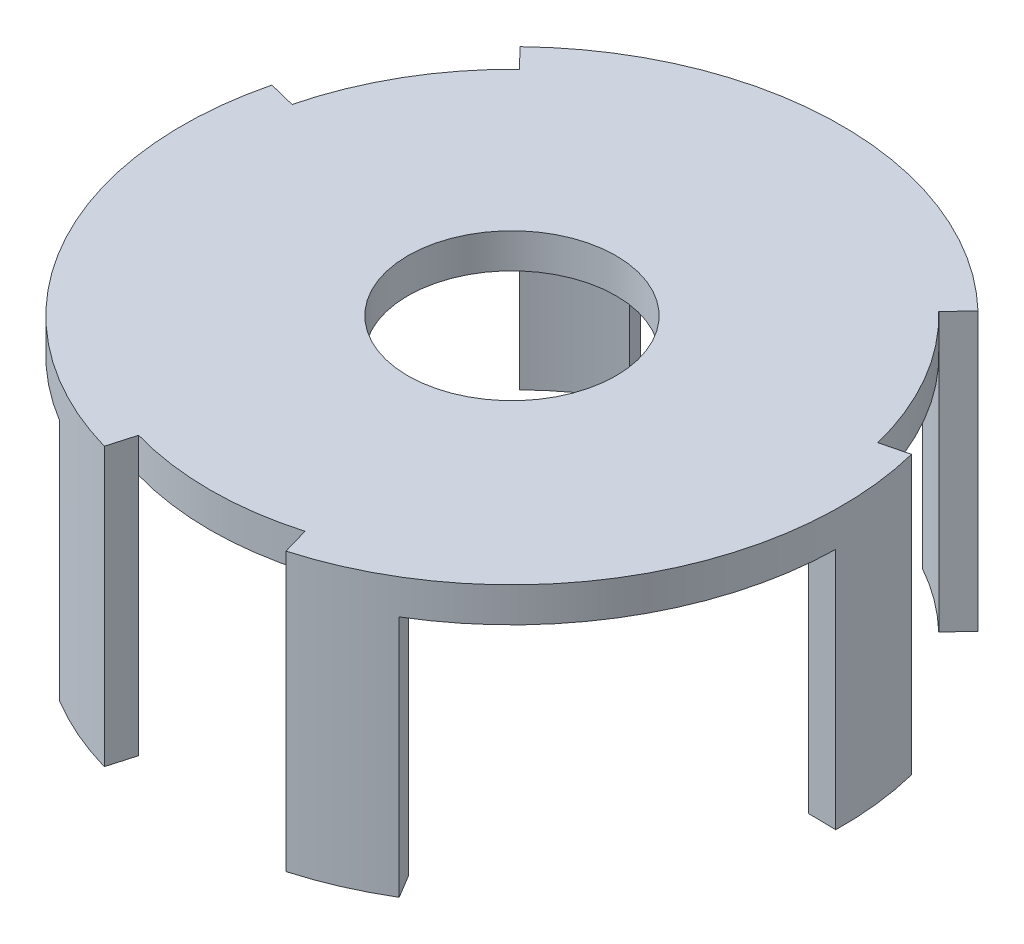
SolidWorks part; units mm, degrees
ref_plane "Alzado" through (0, 0, 0) normal (0, 0, 1) x (1, 0, 0)
ref_plane "Planta" through (0, 0, 0) normal (0, 1, 0) x (1, 0, 0)
ref_plane "Vista lateral" through (0, 0, 0) normal (1, 0, 0) x (0, 0, -1)
sketch "Croquis1" plane through (0, 0, 0) normal (0, 1, 0) x (1, 0, 0)
  circle A0 centre (0, 0) radius 47.5 construction
  dimension "D1" = 95
ref_plane "Plano1" through (0, 40, 0) normal (0, 1, 0) x (1, 0, 0)
sketch "Croquis2" plane through (0, 40, 0) normal (0, 1, 0) x (1, 0, 0)
  circle A0 centre (0, 0) radius 47.5
  circle A1 centre (0, 0) radius 15
  dimension "D1" = 95
  dimension "D2" = 30
extrude "Saliente-Extruir1" add sketch "Croquis2" against normal blind 5
sketch "Croquis3" plane through (0, 35, 0) normal (0, -1, 0) x (1, 0, 0)
  line L0 (-11.9902, 41.8149) -> (-13.0928, 45.6599)
  line L1 (11.9902, 41.8149) -> (13.0928, 45.6599)
  line L2 (0, 0) -> (0, 47.5) construction
  line L3 (-11.9902, 41.8149) -> (0, 0) construction
  line L4 (0, 0) -> (11.9902, 41.8149) construction
  line L5 (30.2176, -31.2913) -> (32.9963, -34.1686)
  line L6 (42.2079, -10.5236) -> (46.089, -11.4913)
  line L7 (-42.2079, -10.5236) -> (-46.089, -11.4913)
  line L8 (-30.2176, -31.2913) -> (-32.9963, -34.1686)
  arc A0 (11.9902, 41.8149) -> (-11.9902, 41.8149) centre (0, 0) ccw
  arc A1 (13.0928, 45.6599) -> (-13.0928, 45.6599) centre (0, 0) ccw
  arc A2 (32.9963, -34.1686) -> (46.089, -11.4913) centre (0, 0) ccw
  arc A3 (30.2176, -31.2913) -> (42.2079, -10.5236) centre (0, 0) ccw
  arc A4 (-46.089, -11.4913) -> (-32.9963, -34.1686) centre (0, 0) ccw
  arc A5 (-42.2079, -10.5236) -> (-30.2176, -31.2913) centre (0, 0) ccw
  point P17 (0, 0)
  dimension "D1" = 87
  dimension "D2" = 95
  dimension "D3" = 32
  dimension "D4" = 16
  dimension "D5" = 3
extrude "Cortar-Extruir1" cut sketch "Croquis3" against normal blind 5
sketch "Croquis4" plane through (0, 35, 0) normal (0, -1, 0) x (1, 0, 0)
  line L0 (-43.4934, 0.7592) -> (0, 0) construction
  line L1 (0, 0) -> (-22.4042, 37.2868) construction
  line L2 (-43.4934, 0.7592) -> (-47.4928, 0.829)
  line L3 (-22.4042, 37.2868) -> (-24.4643, 40.7154)
  line L4 (-42.2079, -10.5236) -> (-46.089, -11.4913)
  line L5 (-11.9902, 41.8149) -> (-13.0928, 45.6599)
  line L6 (0, 0) -> (-42.2079, -10.5236) construction
  line L7 (0, 0) -> (-11.9902, 41.8149) construction
  line L8 (43.4934, 0.7592) -> (47.4928, 0.829)
  line L9 (42.2079, -10.5236) -> (46.089, -11.4913)
  line L10 (22.4042, 37.2868) -> (24.4643, 40.7154)
  line L11 (11.9902, 41.8149) -> (13.0928, 45.6599)
  line L12 (-21.0892, -38.046) -> (-23.0285, -41.5444)
  line L13 (-30.2176, -31.2913) -> (-32.9963, -34.1686)
  line L14 (21.0892, -38.046) -> (23.0285, -41.5444)
  line L15 (30.2176, -31.2913) -> (32.9963, -34.1686)
  circle A1 centre (0, 0) radius 47.5 construction
  arc A2 (-47.4928, 0.829) -> (-46.089, -11.4913) centre (0, 0) ccw
  arc A3 (-43.4934, 0.7592) -> (-42.2079, -10.5236) centre (0, 0) ccw
  arc A4 (-11.9902, 41.8149) -> (-22.4042, 37.2868) centre (0, 0) ccw
  arc A5 (-13.0928, 45.6599) -> (-24.4643, 40.7154) centre (0, 0) ccw
  arc A6 (46.089, -11.4913) -> (47.4928, 0.829) centre (0, 0) ccw
  arc A7 (42.2079, -10.5236) -> (43.4934, 0.7592) centre (0, 0) ccw
  arc A8 (24.4643, 40.7154) -> (13.0928, 45.6599) centre (0, 0) ccw
  arc A9 (22.4042, 37.2868) -> (11.9902, 41.8149) centre (0, 0) ccw
  arc A10 (-32.9963, -34.1686) -> (-23.0285, -41.5444) centre (0, 0) ccw
  arc A11 (-30.2176, -31.2913) -> (-21.0892, -38.046) centre (0, 0) ccw
  arc A12 (23.0285, -41.5444) -> (32.9963, -34.1686) centre (0, 0) ccw
  arc A13 (21.0892, -38.046) -> (30.2176, -31.2913) centre (0, 0) ccw
  point P33 (0, 0)
  dimension "D1" = 3
  dimension "D3" = 15
  dimension "D4" = 15
extrude "Saliente-Extruir2" add sketch "Croquis4" along normal blind 35
